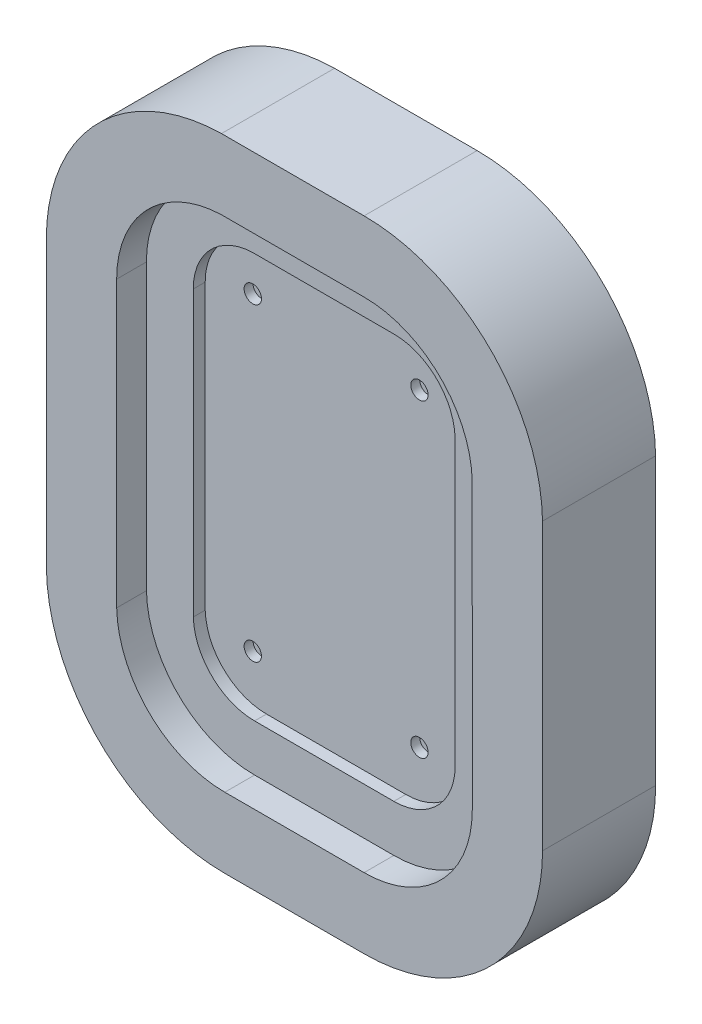
SolidWorks part; units mm, degrees
ref_plane "Front Plane" through (0, 0, 0) normal (0, 0, 1) x (1, 0, 0)
ref_plane "Top Plane" through (0, 0, 0) normal (0, 1, 0) x (1, 0, 0)
ref_plane "Right Plane" through (0, 0, 0) normal (1, 0, 0) x (0, 0, -1)
sketch "Sketch2" plane through (0, 0, 0) normal (0, 0, 1) x (1, 0, 0)
  line L0 (11.1036, 2.9168) -> (-18.6164, 2.9168) construction
  line L1 (-26.6164, 10.9168) -> (-26.6164, 71.1168) construction
  line L2 (-18.6164, 79.1168) -> (11.1036, 79.1168) construction
  line L3 (19.1036, 71.1168) -> (19.1036, 10.9168) construction
  line L4 (11.1036, 2.9168) -> (-18.6164, 2.9168) construction
  line L5 (-26.6164, 10.9168) -> (-26.6164, 71.1168) construction
  line L6 (-18.6164, 79.1168) -> (11.1036, 79.1168) construction
  line L7 (19.1036, 71.1168) -> (19.1036, 10.9168) construction
  line L8 (-24.0764, 10.9168) -> (-24.0764, 71.1175) construction
  line L9 (-18.9921, 81.6527) -> (11.1029, 81.6568) construction
  line L10 (-29.1564, 71.1161) -> (-29.1523, 10.5411) construction
  line L11 (21.6394, 71.4925) -> (21.6436, 10.9168) construction
  line L12 (-18.6157, 0.3768) -> (11.1036, 0.3768) construction
  line L13 (-18.6164, 76.5768) -> (11.1043, 76.5768) construction
  line L14 (16.5636, 71.1168) -> (16.5636, 10.9168) construction
  line L15 (11.1036, 5.4568) -> (-18.6171, 5.4568) construction
  line L16 (-18.6164, 81.6568) -> (11.1029, 81.6568) construction
  line L17 (-29.1564, 10.9168) -> (-29.1564, 71.1161) construction
  line L18 (21.6436, 71.1168) -> (21.6436, 10.9168) construction
  line L19 (11.1036, 0.3768) -> (-18.6157, 0.3768) construction
  line L20 (-19.0349, 84.1927) -> (11.1021, 84.1968) construction
  line L21 (24.1794, 71.5352) -> (24.1836, 10.9169) construction
  line L22 (-18.6151, -2.1632) -> (11.1036, -2.1632) construction
  line L23 (-31.6964, 71.1154) -> (-31.6923, 10.4984) construction
  line L24 (34.1794, 71.6724) -> (34.1836, 10.9173) construction
  line L25 (-18.6129, -12.1632) -> (11.1036, -12.1632) construction
  line L26 (-41.6964, 71.1128) -> (-41.6923, 10.3612) construction
  line L27 (-19.1725, 94.1926) -> (11.0991, 94.1968) construction
  circle A0 centre (14.0236, 74.0368) radius 1.1 construction
  circle A1 centre (-21.5364, 74.0368) radius 1.1 construction
  circle A2 centre (-21.5364, 7.9968) radius 1.1 construction
  circle A3 centre (14.0236, 7.9968) radius 1.1 construction
  arc A4 (11.1036, 2.9168) -> (19.1036, 10.9168) centre (11.1036, 10.9168) ccw construction
  arc A5 (-26.6139, 10.6312) -> (-18.6164, 2.9168) centre (-18.6209, 10.9148) ccw construction
  arc A6 (-18.902, 79.1143) -> (-26.6164, 71.1168) centre (-18.6184, 71.1213) ccw construction
  arc A7 (19.101, 71.4025) -> (11.1036, 79.1168) centre (11.1081, 71.1188) ccw construction
  circle A8 centre (14.0236, 74.0368) radius 1.1 construction
  circle A9 centre (-21.5364, 74.0368) radius 1.1 construction
  circle A10 centre (-21.5364, 7.9968) radius 1.1 construction
  circle A11 centre (14.0236, 7.9968) radius 1.1 construction
  arc A12 (11.1036, 2.9168) -> (19.1036, 10.9168) centre (11.1036, 10.9168) ccw construction
  arc A13 (-26.6139, 10.6312) -> (-18.6164, 2.9168) centre (-18.6209, 10.9148) ccw construction
  arc A14 (-18.902, 79.1143) -> (-26.6164, 71.1168) centre (-18.6184, 71.1213) ccw construction
  arc A15 (19.101, 71.4025) -> (11.1036, 79.1168) centre (11.1081, 71.1188) ccw construction
  arc A16 (-18.812, 76.5759) -> (-24.0764, 71.1175) centre (-18.6184, 71.1213) ccw construction
  arc A17 (21.6394, 71.4925) -> (11.1029, 81.6568) centre (11.1081, 71.1188) ccw construction
  arc A18 (11.1036, 0.3768) -> (21.6436, 10.9168) centre (11.1036, 10.9168) ccw construction
  arc A19 (-29.1523, 10.5411) -> (-18.6157, 0.3768) centre (-18.6209, 10.9148) ccw construction
  arc A20 (-18.9921, 81.6527) -> (-29.1564, 71.1161) centre (-18.6184, 71.1213) ccw construction
  arc A21 (16.5626, 71.3124) -> (11.1043, 76.5768) centre (11.1081, 71.1188) ccw construction
  arc A22 (11.1036, 5.4568) -> (16.5636, 10.9168) centre (11.1036, 10.9168) ccw construction
  arc A23 (-24.0755, 10.7213) -> (-18.6171, 5.4568) centre (-18.6209, 10.9148) ccw construction
  arc A24 (24.1794, 71.5352) -> (11.1021, 84.1968) centre (11.1081, 71.1188) ccw construction
  arc A25 (11.1036, -2.1632) -> (24.1836, 10.9169) centre (11.1036, 10.9168) ccw construction
  arc A26 (-31.6923, 10.4984) -> (-18.6151, -2.1632) centre (-18.6209, 10.9148) ccw construction
  arc A27 (-19.0349, 84.1927) -> (-31.6964, 71.1154) centre (-18.6184, 71.1213) ccw construction
  arc A28 (11.1036, -12.1632) -> (34.1836, 10.9173) centre (11.1036, 10.9168) ccw construction
  arc A29 (-41.6923, 10.3612) -> (-18.6129, -12.1632) centre (-18.6209, 10.9148) ccw construction
  arc A30 (-19.1725, 94.1926) -> (-41.6964, 71.1128) centre (-18.6184, 71.1213) ccw construction
  arc A31 (34.1794, 71.6724) -> (11.0991, 94.1968) centre (11.1081, 71.1188) ccw construction
  dimension "D1" = 2.54
  dimension "D2" = 2.54
  dimension "D3" = 2.54
  dimension "D4" = 10
sketch "Sketch3" plane through (0, 0, 0) normal (0, 0, 1) x (1, 0, 0)
  line L0 (34.1794, 71.6724) -> (34.1836, 10.9173) construction
  line L1 (-18.6129, -12.1632) -> (11.1036, -12.1632) construction
  line L2 (-41.6964, 71.1128) -> (-41.6923, 10.3612) construction
  line L3 (-19.1725, 94.1926) -> (11.0991, 94.1968) construction
  line L4 (34.1794, 71.6724) -> (34.1836, 10.9173)
  line L5 (-18.6129, -12.1632) -> (11.1036, -12.1632)
  line L6 (-41.6964, 71.1128) -> (-41.6923, 10.3612)
  line L7 (-19.1725, 94.1926) -> (11.0991, 94.1968)
  line L8 (49.1794, 71.8305) -> (49.1836, 10.9179)
  line L9 (-18.6102, -27.1632) -> (11.1036, -27.1632)
  line L10 (-56.6964, 71.1095) -> (-56.6922, 10.2031)
  line L11 (-19.3314, 109.1926) -> (11.0952, 109.1968)
  line L12 (-31.6964, 71.1154) -> (-31.6923, 10.4984) construction
  line L13 (-18.6151, -2.1632) -> (11.1036, -2.1632) construction
  line L14 (24.1794, 71.5352) -> (24.1836, 10.9169) construction
  line L15 (-19.0349, 84.1927) -> (11.1021, 84.1968) construction
  line L16 (-31.6964, 71.1154) -> (-31.6923, 10.4984)
  line L17 (-18.6151, -2.1632) -> (11.1036, -2.1632)
  line L18 (24.1794, 71.5352) -> (24.1836, 10.9169)
  line L19 (-19.0349, 84.1927) -> (11.1021, 84.1968)
  arc A0 (11.1036, -12.1632) -> (34.1836, 10.9173) centre (11.1036, 10.9168) ccw construction
  arc A1 (-41.6923, 10.3612) -> (-18.6129, -12.1632) centre (-18.6209, 10.9148) ccw construction
  arc A2 (-19.1725, 94.1926) -> (-41.6964, 71.1128) centre (-18.6184, 71.1213) ccw construction
  arc A3 (34.1794, 71.6724) -> (11.0991, 94.1968) centre (11.1081, 71.1188) ccw construction
  arc A4 (11.1036, -12.1632) -> (34.1836, 10.9173) centre (11.1036, 10.9168) ccw
  arc A5 (-41.6923, 10.3612) -> (-18.6129, -12.1632) centre (-18.6209, 10.9148) ccw
  arc A6 (-19.1725, 94.1926) -> (-41.6964, 71.1128) centre (-18.6184, 71.1213) ccw
  arc A7 (34.1794, 71.6724) -> (11.0991, 94.1968) centre (11.1081, 71.1188) ccw
  arc A8 (11.1036, -27.1632) -> (49.1836, 10.9179) centre (11.1036, 10.9168) ccw
  arc A9 (-56.6922, 10.2031) -> (-18.6102, -27.1632) centre (-18.6209, 10.9148) ccw
  arc A10 (-19.3314, 109.1926) -> (-56.6964, 71.1095) centre (-18.6184, 71.1213) ccw
  arc A11 (49.1794, 71.8305) -> (11.0952, 109.1968) centre (11.1081, 71.1188) ccw
  arc A12 (-31.6923, 10.4984) -> (-18.6151, -2.1632) centre (-18.6209, 10.9148) ccw construction
  arc A13 (11.1036, -2.1632) -> (24.1836, 10.9169) centre (11.1036, 10.9168) ccw construction
  arc A14 (24.1794, 71.5352) -> (11.1021, 84.1968) centre (11.1081, 71.1188) ccw construction
  arc A15 (-19.0349, 84.1927) -> (-31.6964, 71.1154) centre (-18.6184, 71.1213) ccw construction
  arc A16 (-31.6923, 10.4984) -> (-18.6151, -2.1632) centre (-18.6209, 10.9148) ccw
  arc A17 (11.1036, -2.1632) -> (24.1836, 10.9169) centre (11.1036, 10.9168) ccw
  arc A18 (24.1794, 71.5352) -> (11.1021, 84.1968) centre (11.1081, 71.1188) ccw
  arc A19 (-19.0349, 84.1927) -> (-31.6964, 71.1154) centre (-18.6184, 71.1213) ccw
  dimension "D1" = 15
extrude "Boss-Extrude1" add sketch "Sketch3" against normal blind 24.13 from offset 2.54 contours L8 A11 L11 A10 L10 A9 L9 A8 A7 L4 A4 L5 A5 L6 A6 L7
sketch "Sketch4" plane through (0, 0, 0) normal (0, 0, 1) x (1, 0, 0)
  line L0 (-31.6964, 71.1154) -> (-31.6923, 10.4984) construction
  line L1 (-18.6151, -2.1632) -> (11.1036, -2.1632) construction
  line L2 (24.1794, 71.5352) -> (24.1836, 10.9169) construction
  line L3 (-19.0349, 84.1927) -> (11.1021, 84.1968) construction
  line L4 (-18.6129, -12.1632) -> (11.1036, -12.1632) construction
  line L5 (-41.6964, 71.1128) -> (-41.6923, 10.3612) construction
  line L6 (34.1794, 71.6724) -> (34.1836, 10.9173) construction
  line L7 (-19.1725, 94.1926) -> (11.0991, 94.1968) construction
  line L8 (-31.6964, 71.1154) -> (-31.6923, 10.4984)
  line L9 (-18.6151, -2.1632) -> (11.1036, -2.1632)
  line L10 (24.1794, 71.5352) -> (24.1836, 10.9169)
  line L11 (-19.0349, 84.1927) -> (11.1021, 84.1968)
  line L12 (-18.6129, -12.1632) -> (11.1036, -12.1632)
  line L13 (-41.6964, 71.1128) -> (-41.6923, 10.3612)
  line L14 (34.1794, 71.6724) -> (34.1836, 10.9173)
  line L15 (-19.1725, 94.1926) -> (11.0991, 94.1968)
  arc A0 (-19.0349, 84.1927) -> (-31.6964, 71.1154) centre (-18.6184, 71.1213) ccw construction
  arc A1 (-31.6923, 10.4984) -> (-18.6151, -2.1632) centre (-18.6209, 10.9148) ccw construction
  arc A2 (11.1036, -2.1632) -> (24.1836, 10.9169) centre (11.1036, 10.9168) ccw construction
  arc A3 (24.1794, 71.5352) -> (11.1021, 84.1968) centre (11.1081, 71.1188) ccw construction
  arc A4 (11.1036, -12.1632) -> (34.1836, 10.9173) centre (11.1036, 10.9168) ccw construction
  arc A5 (-41.6923, 10.3612) -> (-18.6129, -12.1632) centre (-18.6209, 10.9148) ccw construction
  arc A6 (34.1794, 71.6724) -> (11.0991, 94.1968) centre (11.1081, 71.1188) ccw construction
  arc A7 (-19.1725, 94.1926) -> (-41.6964, 71.1128) centre (-18.6184, 71.1213) ccw construction
  arc A8 (-19.0349, 84.1927) -> (-31.6964, 71.1154) centre (-18.6184, 71.1213) ccw
  arc A9 (-31.6923, 10.4984) -> (-18.6151, -2.1632) centre (-18.6209, 10.9148) ccw
  arc A10 (11.1036, -2.1632) -> (24.1836, 10.9169) centre (11.1036, 10.9168) ccw
  arc A11 (24.1794, 71.5352) -> (11.1021, 84.1968) centre (11.1081, 71.1188) ccw
  arc A12 (11.1036, -12.1632) -> (34.1836, 10.9173) centre (11.1036, 10.9168) ccw
  arc A13 (-41.6923, 10.3612) -> (-18.6129, -12.1632) centre (-18.6209, 10.9148) ccw
  arc A14 (34.1794, 71.6724) -> (11.0991, 94.1968) centre (11.1081, 71.1188) ccw
  arc A15 (-19.1725, 94.1926) -> (-41.6964, 71.1128) centre (-18.6184, 71.1213) ccw
extrude "Boss-Extrude2" add sketch "Sketch4" against normal up to surface (17.78 mm away) from offset 3.81 up to face at (-3.816, 40.9918, -21.59) offset against normal yes
sketch "Sketch5" plane through (0, 0, 0) normal (0, 0, 1) x (1, 0, 0)
  line L0 (-18.6151, -2.1632) -> (11.1036, -2.1632) construction
  line L1 (-31.6964, 71.1154) -> (-31.6923, 10.4984) construction
  line L2 (24.1794, 71.5352) -> (24.1836, 10.9169) construction
  line L3 (-19.0349, 84.1927) -> (11.1021, 84.1968) construction
  line L4 (-18.6151, -2.1632) -> (11.1036, -2.1632)
  line L5 (-31.6964, 71.1154) -> (-31.6923, 10.4984)
  line L6 (24.1794, 71.5352) -> (24.1836, 10.9169)
  line L7 (-19.0349, 84.1927) -> (11.1021, 84.1968)
  arc A0 (11.1036, -2.1632) -> (24.1836, 10.9169) centre (11.1036, 10.9168) ccw construction
  arc A1 (-31.6923, 10.4984) -> (-18.6151, -2.1632) centre (-18.6209, 10.9148) ccw construction
  arc A2 (24.1794, 71.5352) -> (11.1021, 84.1968) centre (11.1081, 71.1188) ccw construction
  arc A3 (-19.0349, 84.1927) -> (-31.6964, 71.1154) centre (-18.6184, 71.1213) ccw construction
  arc A4 (11.1036, -2.1632) -> (24.1836, 10.9169) centre (11.1036, 10.9168) ccw
  arc A5 (-31.6923, 10.4984) -> (-18.6151, -2.1632) centre (-18.6209, 10.9148) ccw
  arc A6 (24.1794, 71.5352) -> (11.1021, 84.1968) centre (11.1081, 71.1188) ccw
  arc A7 (-19.0349, 84.1927) -> (-31.6964, 71.1154) centre (-18.6184, 71.1213) ccw
extrude "Boss-Extrude3" add sketch "Sketch5" against normal up to surface (15.24 mm away) from offset 6.35 up to face at (-3.8332, 40.9845, -21.59) offset against normal yes
sketch "Sketch6" plane through (0, 0, -6.35) normal (0, 0, 1) x (1, 0, 0)
  circle A0 centre (-21.5364, 7.9968) radius 1.1 construction
  circle A1 centre (14.0236, 7.9968) radius 1.1 construction
  circle A2 centre (14.0236, 74.0368) radius 1.1 construction
  circle A3 centre (-21.5364, 74.0368) radius 1.1 construction
  circle A4 centre (-21.5364, 7.9968) radius 1.1 construction
  circle A5 centre (14.0236, 7.9968) radius 1.1 construction
  circle A6 centre (14.0236, 74.0368) radius 1.1 construction
  circle A7 centre (-21.5364, 74.0368) radius 1.1 construction
  circle A8 centre (-21.5364, 74.0368) radius 1.85
  circle A9 centre (14.0236, 74.0368) radius 1.85
  circle A10 centre (14.0236, 7.9968) radius 1.85
  circle A11 centre (-21.5364, 7.9968) radius 1.85
  point P13 (0, 0)
  point P16 (13.2048, 74.0368)
  point P18 (12.9236, 7.9968)
  point P20 (-21.5364, 9.0968)
  dimension "D1" = 3.7
extrude "Cut-Extrude1" cut sketch "Sketch6" against normal blind 1.905
